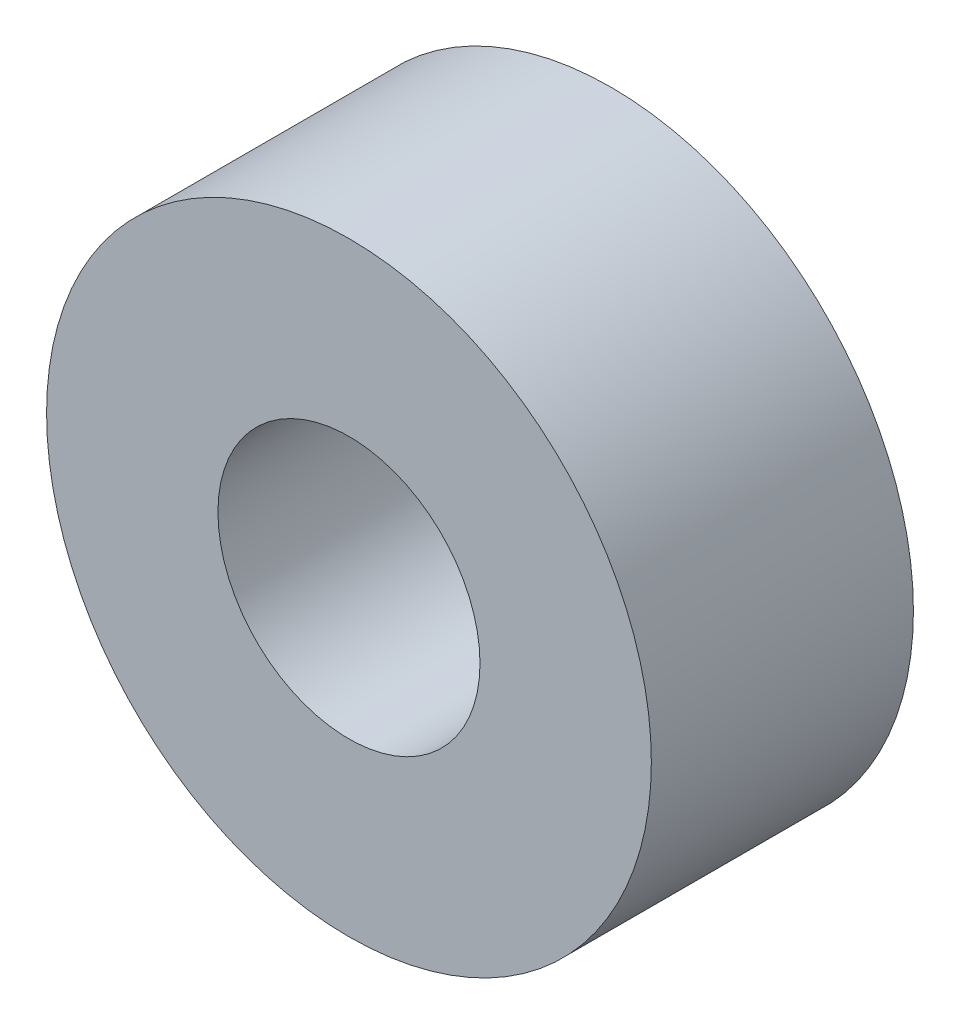
SolidWorks part; units mm, degrees
ref_plane "Front Plane" through (0, 0, 0) normal (0, 0, 1) x (1, 0, 0)
ref_plane "Top Plane" through (0, 0, 0) normal (0, 1, 0) x (1, 0, 0)
ref_plane "Right Plane" through (0, 0, 0) normal (1, 0, 0) x (0, 0, -1)
sketch "Sketch1" plane through (0, 0, 0) normal (0, 0, 1) x (1, 0, 0)
  circle A0 centre (0, 0) radius 7.5
  dimension "D1" = 15
extrude "Boss-Extrude1" add sketch "Sketch1" along normal blind 6.5
sketch "Sketch3" plane through (0, 0, 0) normal (0, 0, -1) x (-1, 0, 0)
  circle A0 centre (0, 0) radius 3.25
  dimension "D1" = 6.5
extrude "Cut-Extrude1" cut sketch "Sketch3" against normal blind 10 contours A0
